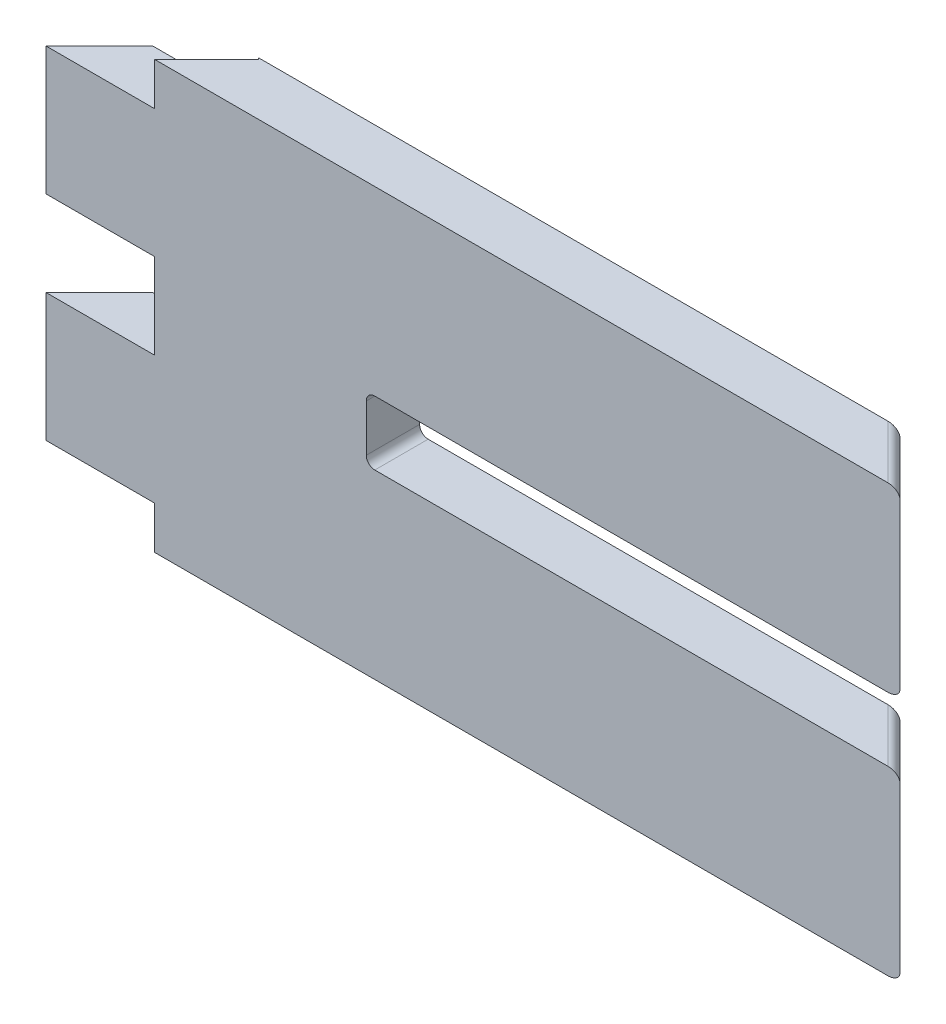
SolidWorks part; units mm, degrees
ref_plane "Front Plane" through (0, 0, 0) normal (0, 0, 1) x (1, 0, 0)
ref_plane "Top Plane" through (0, 0, 0) normal (0, 1, 0) x (1, 0, 0)
ref_plane "Right Plane" through (0, 0, 0) normal (1, 0, 0) x (0, 0, -1)
sketch "Sketch1" plane through (0, 0, 0) normal (0, 0, 1) x (1, 0, 0)
  line L0 (20, -1.5) -> (20, -8)
  line L1 (-20, 8) -> (20, 8)
  line L2 (-20, 8) -> (-20, -8)
  line L3 (-20, -8) -> (20, -8)
  line L4 (20, 8) -> (20, 1.5)
  line L5 (-20, 8) -> (20, -8) construction
  line L6 (-20, -8) -> (20, 8) construction
  line L7 (-5, -1.5) -> (20, -1.5)
  line L8 (-5, -1.5) -> (-5, 1.5)
  line L9 (-5, 1.5) -> (20, 1.5)
  point P0 (0, 0)
  point P11 (-5, 0)
  dimension "D1" = 40
  dimension "D2" = 16
  dimension "D3" = 3
  dimension "D4" = 5
extrude "Boss-Extrude1" add sketch "Sketch1" along normal blind 2.5
sketch "Sketch2" plane through (0, 8, 0) normal (0, 1, 0) x (1, 0, 0)
  line L0 (20, -2.5) -> (17.5, 0)
  line L1 (20, 0) -> (-20, 0) construction
  line L2 (17.5, 0) -> (20, 0)
  line L3 (20, 0) -> (20, -2.5)
extrude "Cut-Extrude1" cut sketch "Sketch2" against normal through all
sketch "Sketch5" plane through (0, 8, 0) normal (0, 1, 0) x (1, 0, 0)
  line L0 (-20, -2.5) -> (-17.5, 0)
  line L1 (17.5, 0) -> (-20, 0) construction
  line L2 (-17.5, 0) -> (-20, 0)
  line L3 (-20, -2.5) -> (-20, 0) construction
  line L4 (-20, 0) -> (-20, -2.5)
extrude "Cut-Extrude2" cut sketch "Sketch5" against normal through all
sketch "Sketch6" plane through (0, 8, 0) normal (0, 1, 0) x (1, 0, 0)
  line L0 (-17.5, 0) -> (-23.5357, -6.0357) construction
  line L1 (-23.5357, -6.0357) -> (-18.586, -6.0357) construction
  line L2 (-18.586, -6.0357) -> (-12.5503, 0) construction
  line L3 (17.5, 0) -> (-17.5, 0) construction
  line L4 (-12.5503, 0) -> (-17.5, 0) construction
  line L5 (-12.5503, 0) -> (-15.0503, -2.5)
  line L6 (20, -2.5) -> (-20, -2.5) construction
  line L7 (-15.0503, -2.5) -> (20, -2.5)
  line L8 (20, -2.5) -> (17.5, 0)
  line L9 (17.5, 0) -> (-12.5503, 0)
  dimension "D1" = 3.5
extrude "Boss-Extrude2" add sketch "Sketch6" along normal blind 2
sketch "Sketch7" plane through (0, -8, 0) normal (0, -1, 0) x (1, 0, 0)
  line L0 (-17.5, 0) -> (-23.6602, 6.1602) construction
  line L1 (-23.6602, 6.1602) -> (-18.7104, 6.1602) construction
  line L2 (-18.7104, 6.1602) -> (-12.5503, 0) construction
  line L3 (-17.5, 0) -> (17.5, 0) construction
  line L4 (-12.5503, 0) -> (-17.5, 0) construction
  line L5 (-12.5503, 0) -> (17.5, 0)
  line L6 (17.5, 0) -> (20, 2.5)
  line L7 (20, 2.5) -> (-15.0503, 2.5)
  line L8 (-20, 2.5) -> (20, 2.5) construction
  line L9 (-15.0503, 2.5) -> (-12.5503, 0)
  dimension "D1" = 3.5
extrude "Boss-Extrude3" add sketch "Sketch7" along normal blind 2
sketch "Sketch8" plane through (0, 0, 0) normal (0, 1, 0) x (1, 0, 0)
  line L4 (-15.0503, -2.5) -> (-12.5503, 0)
  line L5 (-20, -2.5) -> (-15.0503, -2.5)
  line L6 (-17.5, 0) -> (-20, -2.5)
  line L7 (-12.5503, 0) -> (-17.5, 0)
  line L8 (-15.0503, -2.5) -> (-12.5503, 0)
  line L9 (-20, -2.5) -> (-15.0503, -2.5)
  line L10 (-17.5, 0) -> (-20, -2.5)
  line L11 (-12.5503, 0) -> (-17.5, 0)
  dimension "D1" = 0
extrude "Cut-Extrude3" cut sketch "Sketch8" against normal blind 2 and the other way blind 2
sketch "Sketch9" plane through (-6.2751, 0, -6.2751) normal (-0.7071, 0, -0.7071) x (-0.7071, 0, 0.7071)
  line L0 (8.8744, 8) -> (12.4099, 8) construction
  line L1 (12.4099, 8) -> (12.4099, 10) construction
  line L2 (12.4099, 10) -> (8.8744, 10) construction
  line L3 (8.8744, 10) -> (8.8744, 8) construction
  line L4 (12.4099, -2) -> (12.4099, 2) construction
  line L5 (12.4099, 2) -> (8.8744, 2) construction
  line L6 (8.8744, 2) -> (8.8744, -2) construction
  line L7 (8.8744, -2) -> (12.4099, -2) construction
  line L8 (12.4099, -8) -> (8.8744, -8) construction
  line L9 (8.8744, -8) -> (8.8744, -10) construction
  line L10 (8.8744, -10) -> (12.4099, -10) construction
  line L11 (12.4099, -10) -> (12.4099, -8) construction
  line L12 (8.8744, 8) -> (12.4099, 8)
  line L13 (12.4099, 8) -> (12.4099, 10)
  line L14 (12.4099, 10) -> (8.8744, 10)
  line L15 (8.8744, 10) -> (8.8744, 8)
  line L16 (12.4099, -2) -> (12.4099, 2)
  line L17 (12.4099, 2) -> (8.8744, 2)
  line L18 (8.8744, 2) -> (8.8744, -2)
  line L19 (8.8744, -2) -> (12.4099, -2)
  line L20 (12.4099, -8) -> (8.8744, -8)
  line L21 (8.8744, -8) -> (8.8744, -10)
  line L22 (8.8744, -10) -> (12.4099, -10)
  line L23 (12.4099, -10) -> (12.4099, -8)
extrude "Cut-Extrude5" cut sketch "Sketch9" against normal blind 0.1
sketch "Sketch10" plane through (0, 0, 0) normal (0, 0, -1) x (-1, 0, 0)
  line L0 (-17.5, -10) -> (-17.5, -1.5) construction
  line L1 (-15.9, -8.4) -> (5, -8.4)
  line L2 (-15.9, -8.4) -> (-15.9, -3.1)
  line L3 (-15.9, -3.1) -> (5, -3.1)
  line L4 (5, -8.4) -> (5, -3.1)
  line L5 (5, 3.1036) -> (-15.9, 3.1036)
  line L6 (5, 3.1036) -> (5, 8.4)
  line L7 (5, 8.4) -> (-15.9, 8.4)
  line L8 (-15.9, 3.1036) -> (-15.9, 8.4)
  line L9 (10.9503, -8.4) -> (6.6, -8.4)
  line L10 (10.9503, -8.4) -> (10.9503, 8.4)
  line L11 (10.9503, 8.4) -> (6.6, 8.4)
  line L12 (6.6, -8.4) -> (6.6, 8.4)
  line L13 (-17.5, 1.5) -> (-17.5, 10) construction
  line L14 (-17.5, -1.5) -> (5, -1.5) construction
  line L15 (12.5503, -10) -> (-17.5, -10) construction
  line L16 (5, 1.5) -> (-17.5, 1.5) construction
  line L17 (-17.5, 10) -> (12.5503, 10) construction
  line L18 (5, -1.5) -> (5, 1.5) construction
  line L19 (12.5503, 2) -> (12.5503, -2) construction
  dimension "D1" = 1.6
  dimension "D2" = 1.6
  dimension "D3" = 1.6
  dimension "D4" = 1.6
  dimension "D5" = 1.6036
  dimension "D6" = 1.6
  dimension "D9" = 1.6
  dimension "D10" = 1.6
  dimension "D11" = 1.6
  dimension "D12" = 1.6
extrude "Cut-Extrude6" cut sketch "Sketch10" against normal blind 1.2
fillet "Fillet1" radius 0.4 18 edges at (-5, 1.5, 1.25) (-5, -1.5, 1.25) (-10.9503, 8.4, 0.6) (-10.9503, -8.4, 0.6) (-6.6, -8.4, 0.6) (-6.6, 8.4, 0.6) (-5, 8.4, 0.6) (-5, 3.1036, 0.6) (15.9, 3.1036, 0.6) (15.9, 8.4, 0.6) (15.9, -8.4, 0.6) (15.9, -3.1, 0.6) (-5, -3.1, 0.6) (-5, -8.4, 0.6) (18.75, -1.5, 1.25) (18.75, 1.5, 1.25) (18.75, 10, 1.25) (18.75, -10, 1.25)
